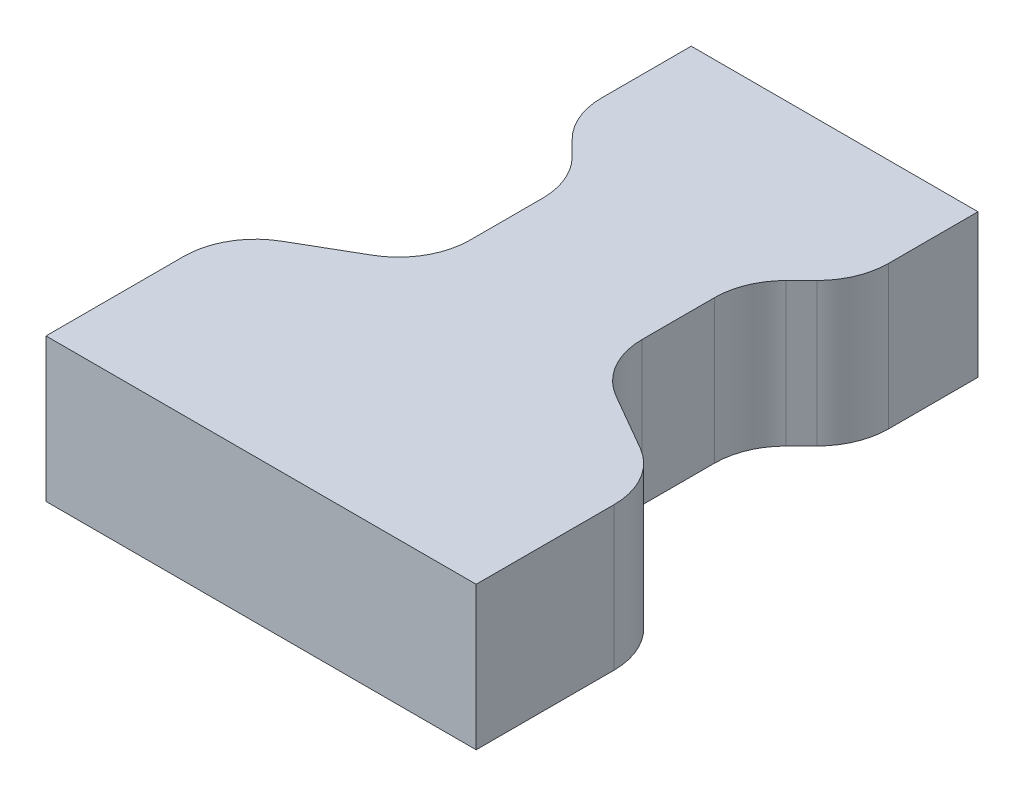
SolidWorks part; units mm, degrees
ref_plane "Front Plane" through (0, 0, 0) normal (0, 0, 1) x (1, 0, 0)
ref_plane "Top Plane" through (0, 0, 0) normal (0, 1, 0) x (1, 0, 0)
ref_plane "Right Plane" through (0, 0, 0) normal (1, 0, 0) x (0, 0, -1)
sketch "Sketch1" plane through (0, 0, 0) normal (0, 1, 0) x (1, 0, 0)
  line L0 (-300, 0) -> (300, 0)
  line L1 (300, 0) -> (300, 192.265)
  line L2 (250, 278.8675) -> (170, 325.0555)
  line L3 (120, 411.6581) -> (120, 512.5017)
  line L4 (149.2893, 583.2124) -> (170.7107, 604.6337)
  line L5 (200, 675.3444) -> (200, 800)
  line L6 (200, 800) -> (-200, 800)
  line L7 (0, -440) -> (0, 440) construction
  line L8 (-200, 675.3444) -> (-200, 800)
  line L9 (-149.2893, 583.2124) -> (-170.7107, 604.6337)
  line L10 (-120, 411.6581) -> (-120, 512.5017)
  line L11 (-250, 278.8675) -> (-170, 325.0555)
  line L12 (-300, 0) -> (-300, 192.265)
  arc A0 (200, 675.3444) -> (170.7107, 604.6337) centre (100, 675.3444) cw
  arc A1 (120, 512.5017) -> (149.2893, 583.2124) centre (220, 512.5017) cw
  arc A2 (170, 325.0555) -> (120, 411.6581) centre (220, 411.6581) cw
  arc A3 (250, 278.8675) -> (300, 192.265) centre (200, 192.265) cw
  arc A4 (-250, 278.8675) -> (-300, 192.265) centre (-200, 192.265) ccw
  arc A5 (-170, 325.0555) -> (-120, 411.6581) centre (-220, 411.6581) ccw
  arc A6 (-120, 512.5017) -> (-149.2893, 583.2124) centre (-220, 512.5017) ccw
  arc A7 (-200, 675.3444) -> (-170.7107, 604.6337) centre (-100, 675.3444) ccw
  point P0 (-300, 250)
  point P13 (120, 553.923)
  point P16 (120, 353.923)
  point P19 (300, 250)
  point P20 (0, 0)
  point P36 (0, 800)
  point P37 (0, 0)
  point P38 (-120, 353.923)
  point P39 (-120, 553.923)
  dimension "D10" = 100
  dimension "D1" = 800
  dimension "D2" = 300
  dimension "D4" = 250
  dimension "D5" = 120
  dimension "D6" = 200
  dimension "D7" = 200
  dimension "D8" = 120
  dimension "D9" = 135
extrude "Boss-Extrude1" add sketch "Sketch1" along normal mid plane 200
